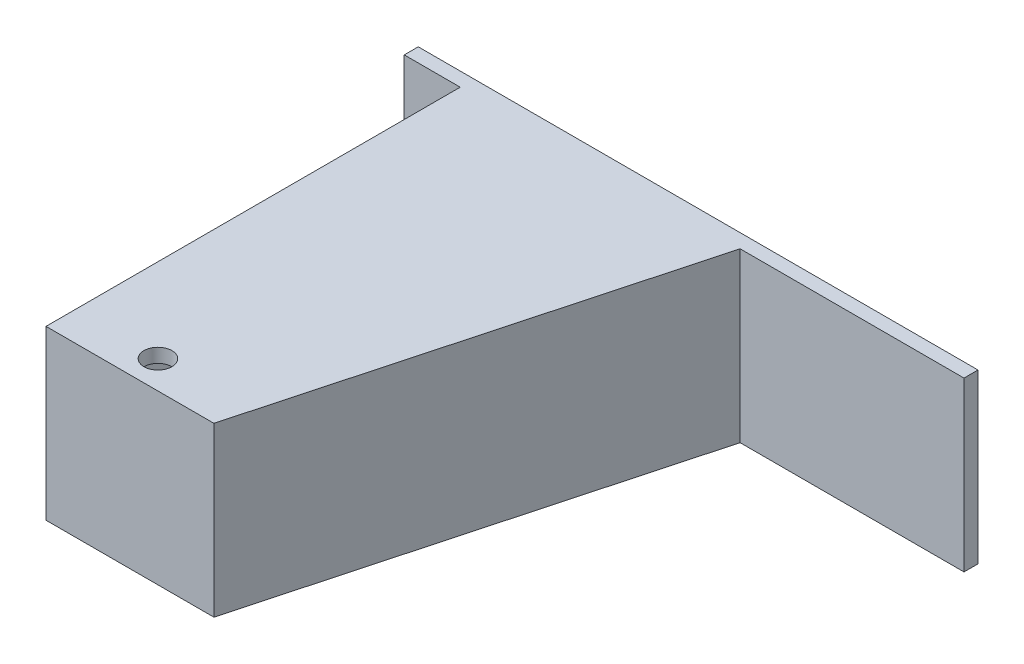
SolidWorks part; units mm, degrees
ref_plane "Front" through (0, 0, 0) normal (0, 0, 1) x (1, 0, 0)
ref_plane "Top" through (0, 0, 0) normal (0, 1, 0) x (1, 0, 0)
ref_plane "Right" through (0, 0, 0) normal (1, 0, 0) x (0, 0, -1)
sketch "Sketch1" plane through (0, 0, 0) normal (0, 1, 0) x (1, 0, 0)
  line L0 (0, 0) -> (0, 93.98)
  line L1 (0, 93.98) -> (-12.7, 93.98)
  line L2 (-12.7, 93.98) -> (-12.7, 97.155)
  line L3 (-12.7, 97.155) -> (114.3, 97.155)
  line L4 (114.3, 97.155) -> (114.3, 93.98)
  line L5 (114.3, 93.98) -> (63.5, 93.98)
  line L6 (63.5, 93.98) -> (38.1, 0)
  line L7 (38.1, 0) -> (0, 0)
  line L8 (-6.35, 93.98) -> (-6.35, 97.155)
  line L9 (88.9, 93.98) -> (88.9, 97.155)
  line L10 (12.7, 6.35) -> (12.7, 0)
  line L11 (19.05, 0) -> (25.4, 0)
  line L12 (19.05, 0) -> (19.05, 6.35)
  line L13 (19.05, 6.35) -> (25.4, 6.35)
  line L14 (25.4, 0) -> (25.4, 6.35)
  line L15 (19.05, 6.35) -> (19.05, 135.382)
  line L16 (19.05, 6.35) -> (48.2655, 168.651)
  line L17 (88.9, 97.155) -> (88.9, 103.505)
  line L18 (82.55, 103.505) -> (82.55, 97.155)
  line L19 (95.25, 103.505) -> (95.25, 97.155)
  line L20 (19.05, 135.382) -> (88.9, 103.505)
  line L21 (48.2655, 168.651) -> (88.9, 103.505)
  line L22 (35.6692, 3.175) -> (3.175, 3.175)
  line L23 (3.175, 3.175) -> (3.175, 93.98)
  line L24 (3.175, 93.98) -> (3.175, 93.98)
  line L25 (3.175, 93.98) -> (3.175, 93.98)
  line L26 (3.175, 93.98) -> (60.2111, 93.98)
  line L27 (60.2111, 93.98) -> (60.2111, 93.98)
  line L28 (60.2111, 93.98) -> (60.2111, 93.98)
  line L29 (60.2111, 93.98) -> (35.6692, 3.175)
  line L31 (3.175, 93.98) -> (60.2111, 93.98)
  line L32 (3.175, 93.98) -> (3.175, 97.155)
  line L33 (3.175, 97.155) -> (60.2111, 97.155)
  line L34 (60.2111, 93.98) -> (60.2111, 97.155)
  circle A0 centre (19.05, 6.35) radius 6.35
  circle A1 centre (19.05, 6.35) radius 3.175
  circle A2 centre (88.9, 103.505) radius 6.35
  circle A3 centre (88.9, 103.505) radius 3.175
  dimension "D10" = 6.35
  dimension "D14" = 6.35
  dimension "D1" = 3.175
  dimension "D2" = 12.7
  dimension "D3" = 50.8
  dimension "D4" = 38.1
  dimension "D5" = 93.98
  dimension "D6" = 127
  dimension "D7" = 3.175
  dimension "D8" = 6.35
  dimension "D9" = 6.35
  dimension "D11" = 3.175
  dimension "D13" = 6.35
extrude "Boss-Extrude1" add sketch "Sketch1" along normal blind 38.1 contours A1 L15 A0 L22 | A0 L22 L10 L7 | L34 L29 L22 L14 L7 L6 L5 L9 L3 | A1 L16 A0 L15 | A1 L13 A0 L16 | A0 L7 L14 L22 | L22 A0 L12 | L12 A0 L22 | A1 L22 A0 L13 | L23 L32 L3 L8 L1 L0 L7 L10 L22 | A0 L14 L22 L29 L26 L16 | A0 L22 L14 | A0 L15 L26 L23 L22 L10 | A0 L10 L22 | A0 L16 L26 L15 | L9 L5 L4 L3 | L1 L8 L3 L2
sketch "Sketch2" plane through (0, 0, 0) normal (0, -1, 0) x (1, 0, 0)
  line L0 (60.2111, -97.155) -> (60.2111, -93.98)
  line L1 (60.2111, -93.98) -> (35.6692, -3.175)
  line L2 (35.6692, -3.175) -> (3.175, -3.175)
  line L3 (3.175, -3.175) -> (3.175, -93.98)
  line L4 (3.175, -93.98) -> (3.175, -97.155)
  line L5 (3.175, -97.155) -> (60.2111, -97.155)
extrude "Cut-Extrude1" cut sketch "Sketch2" against normal offset from surface (31.75 mm away) 3.175 from offset 3.175
